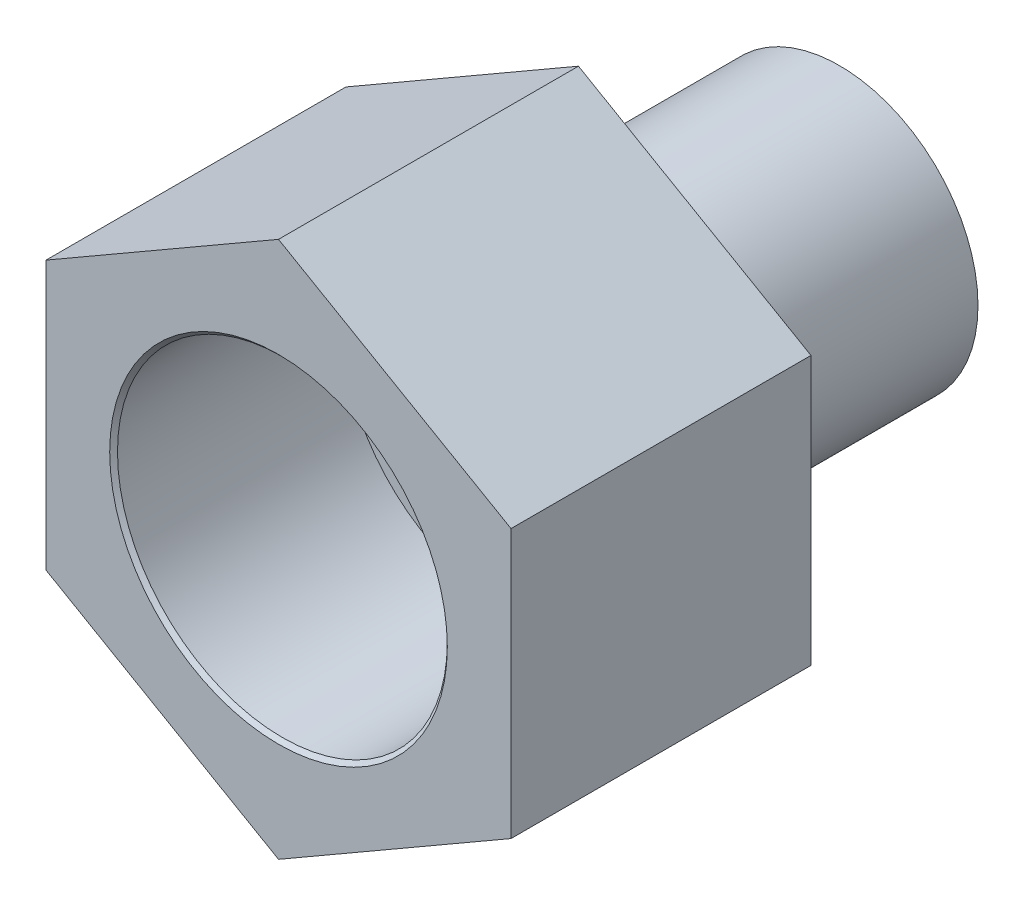
SolidWorks part; units mm, degrees
other "ElementoDettaglio1"
ref_plane "Piano frontale" through (0, 0, 0) normal (0, 0, 1) x (1, 0, 0)
ref_plane "Piano superiore" through (0, 0, 0) normal (0, 1, 0) x (1, 0, 0)
ref_plane "Piano destro" through (0, 0, 0) normal (1, 0, 0) x (0, 0, -1)
sketch "Schizzo10" plane through (0, 0, 0) normal (0, 0, 1) x (1, 0, 0)
  circle A0 centre (0, 0) radius 20.675
  dimension "D1" = 41.35
extrude "Estrusione-Estrusione5" add sketch "Schizzo10" against normal blind 43.2
sketch "Schizzo16" plane through (0, 0, 0) normal (0, 0, 1) x (1, 0, 0)
  line L1 (0, 20.675) -> (-17.9051, 10.3375)
  line L2 (-17.9051, 10.3375) -> (-17.9051, -10.3375)
  line L3 (-17.9051, -10.3375) -> (0, -20.675)
  line L4 (0, -20.675) -> (17.9051, -10.3375)
  line L5 (17.9051, -10.3375) -> (17.9051, 10.3375)
  line L6 (17.9051, 10.3375) -> (0, 20.675)
  circle A0 centre (0, 0) radius 17.9051 construction
  circle M1 centre (0, 0) radius 20.675
extrude "Taglio-Estrusione11" cut sketch "Schizzo16" against normal blind 23.1 contours L1 M1 | L6 M1 | L2 M1 | L3 M1 | L4 M1 | L5 M1
hole_wizard "Foro Ø25.5 (25.4)-1" positions "Schizzo18" profile "Schizzo19" hole size "Ø25.5" standard "ISO"
sketch "Schizzo18" plane through (0, 0, 0) normal (0, 0, 1) x (1, 0, 0)
  point P0 (0, 0)
sketch "Schizzo19" plane through (0, 0, 0) normal (1, 0, 0) x (0, -1, 0)
  line L0 (0, 0) -> (0, 17.6)
  line L1 (0, 17.6) -> (12.7, 17.6)
  line L2 (12.7, 17.6) -> (12.7, 0.3)
  line L3 (12.7, 0.3) -> (13, 0)
  line L5 (13, 0) -> (0, 0)
  line L6 (-12.7, 0.3) -> (-13, 0) construction
  line L10 (0, 17.6) -> (-12.7, 17.6) construction
  line L11 (0, -6.35) -> (0, 107.95) construction
  dimension "Hole Dia." = 25.4
  dimension "Hole Depth" = 17.6
  dimension "Near C'Sink Dia." = 26
  dimension "Near C'Sink Angle" = 90
  dimension "Drill Angle" = 180
hole_wizard "Foro Ø25.5 (12.7)-1" positions "Schizzo22" profile "Schizzo23" hole size "Ø25.5" standard "ISO" end condition through all
sketch "Schizzo22" plane through (0, 0, -17.6) normal (0, 0, 1) x (1, 0, 0)
  point P0 (0, 0)
sketch "Schizzo23" plane through (0, 0, -17.6) normal (1, 0, 0) x (0, -1, 0)
  line L0 (0, 0) -> (0, 25.6)
  line L1 (0, 25.6) -> (6.35, 25.6)
  line L2 (6.35, 25.6) -> (6.35, 0)
  line L5 (6.35, 0) -> (0, 0)
  line L11 (0, -6.35) -> (0, 107.95) construction
  dimension "Thru Hole Dia." = 12.7
  dimension "Thru Hole Depth" = 25.6
sketch "Schizzo24" plane through (0, 0, -43.2) normal (0, 0, -1) x (-1, 0, 0)
  circle A0 centre (0, 0) radius 10.668
  circle M3 centre (0, 0) radius 20.675
  dimension "D1" = 21.336
extrude "Taglio-Estrusione12" cut sketch "Schizzo24" along a picked direction on the side against the normal blind 20.1 contours A0 M3
cosmetic thread "Cosmetic Thread1" parameters "D1"=5, "D2"=18.631
